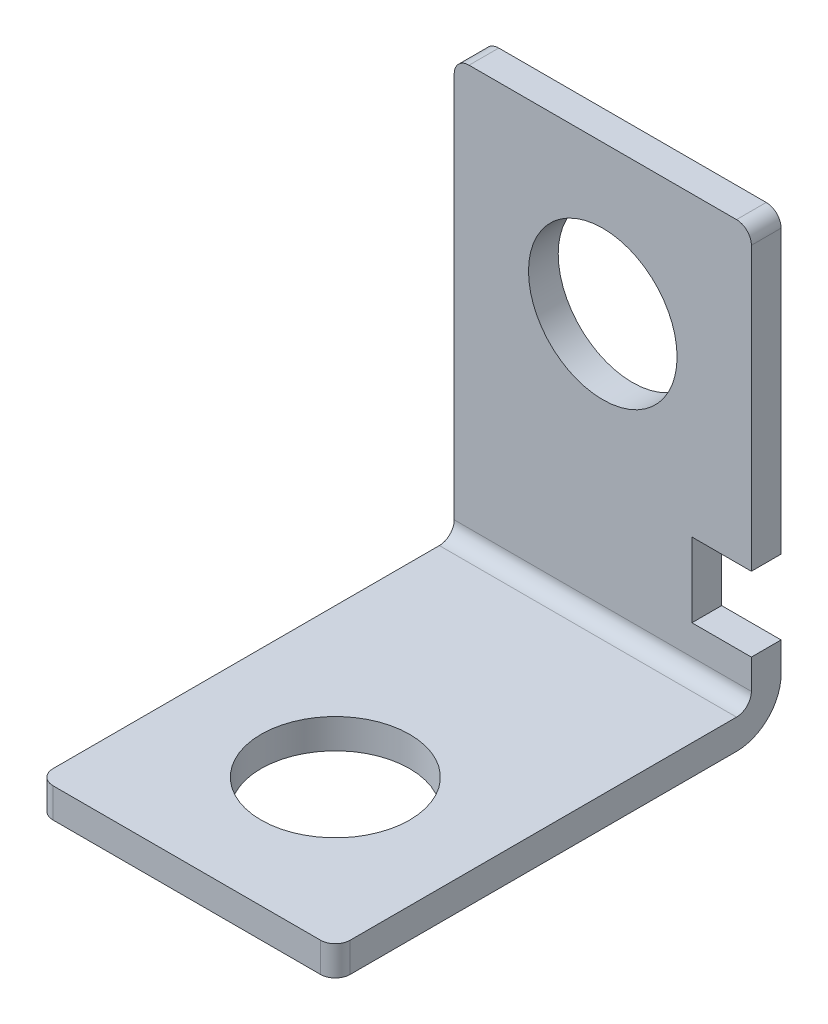
SolidWorks part; units mm, degrees
material "6061 Alloy"
ref_plane "Front Plane" through (0, 0, 0) normal (0, 0, 1) x (1, 0, 0)
ref_plane "Top Plane" through (0, 0, 0) normal (0, 1, 0) x (1, 0, 0)
ref_plane "Right Plane" through (0, 0, 0) normal (1, 0, 0) x (0, 0, -1)
sketch "Sketch5" plane through (0, 0, 0) normal (0, 1, 0) x (1, 0, 0)
  line L1 (0, 0) -> (20, 0)
  line L2 (0, 0) -> (0, 30)
  line L3 (0, 30) -> (20, 30)
  line L4 (20, 0) -> (20, 30)
  circle A0 centre (10, 10) radius 5
  point P7 (0, 0)
  dimension "D5" = 10
  dimension "D1" = 20
  dimension "D2" = 30
  dimension "D3" = 10
  dimension "D4" = 10
extrude "Boss-Extrude3" add sketch "Sketch5" along normal blind 2
sketch "Sketch7" plane through (0, 0, -30) normal (0, 0, -1) x (-1, 0, 0)
  line L0 (-20, 10) -> (-16, 10)
  line L1 (0, 0) -> (-20, 0)
  line L2 (0, 0) -> (0, 30)
  line L3 (0, 30) -> (-20, 30)
  line L4 (-20, 0) -> (-20, 5)
  line L5 (-16, 10) -> (-16, 5)
  line L6 (-16, 5) -> (-20, 5)
  line L7 (-20, 10) -> (-20, 30)
  circle A0 centre (-10, 20) radius 5
  dimension "D8" = 10
  dimension "D1" = 30
  dimension "D2" = 20
  dimension "D3" = 20
  dimension "D4" = 5
  dimension "D5" = 4
  dimension "D6" = 10
  dimension "D7" = 10
extrude "Boss-Extrude4" add sketch "Sketch7" against normal blind 2
fillet "Fillet3" radius 1 5 edges at (10, 2, -28) (0, 30, -29) (20, 30, -29) (0, 1, 0) (20, 1, 0)
fillet "Fillet4" radius 3 1 edges at (10, 0, -30)
